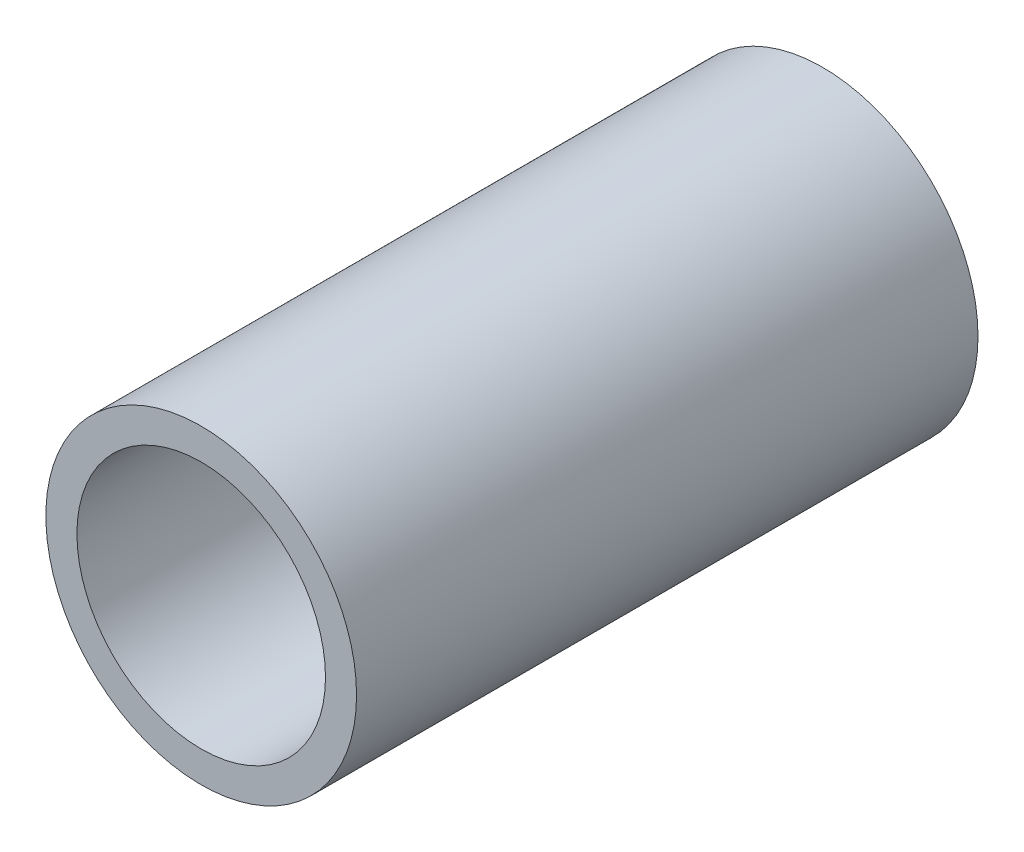
SolidWorks part; units mm, degrees
ref_plane "Front Plane" through (0, 0, 0) normal (0, 0, 1) x (1, 0, 0)
ref_plane "Top Plane" through (0, 0, 0) normal (0, 1, 0) x (1, 0, 0)
ref_plane "Right Plane" through (0, 0, 0) normal (1, 0, 0) x (0, 0, -1)
sketch "Sketch1" plane through (0, 0, 0) normal (0, 0, 1) x (1, 0, 0)
  circle A3 centre (0, 0) radius 63.5
  dimension "D1" = 127
extrude "Boss-Extrude1" add sketch "Sketch1" along normal mid plane 254
sketch "Sketch2" plane through (0, 0, 127) normal (0, 0, 1) x (1, 0, 0)
  circle A0 centre (0, 0) radius 50.8
  dimension "D1" = 101.6
extrude "Cut-Extrude1" cut sketch "Sketch2" against normal through all
